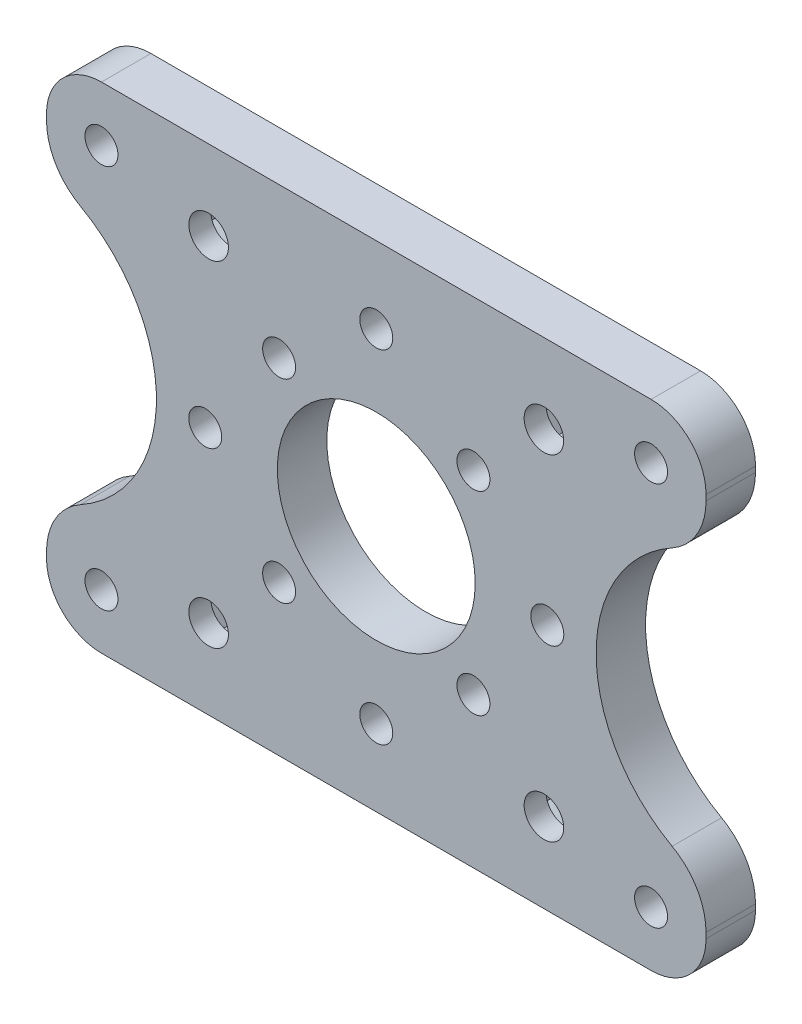
SolidWorks part; units mm, degrees
material "Tough PLA"
ref_plane "前视基准面" through (0, 0, 0) normal (0, 0, 1) x (1, 0, 0)
ref_plane "上视基准面" through (0, 0, 0) normal (0, 1, 0) x (1, 0, 0)
ref_plane "右视基准面" through (0, 0, 0) normal (1, 0, 0) x (0, 0, -1)
sketch "草图1" plane through (0, 0, 0) normal (0, 0, 1) x (1, 0, 0)
  line L0 (0, 20.9217) -> (0, -23.8045) construction
  line L1 (8.8388, 8.8388) -> (0, 0) construction
  line L6 (-30, 0) -> (30, 0) construction
  line L7 (-30, 22.5) -> (30, 22.5)
  line L8 (-30, 22.5) -> (-30, -22.5)
  line L9 (-30, -22.5) -> (30, -22.5)
  line L10 (30, 22.5) -> (30, -22.5)
  line L11 (-30, 22.5) -> (30, -22.5) construction
  line L12 (-30, -22.5) -> (30, 22.5) construction
  line L13 (-25, 17.5) -> (25, 17.5) construction
  line L14 (-25, 17.5) -> (-25, -17.5) construction
  line L15 (-25, -17.5) -> (25, -17.5) construction
  line L16 (25, 17.5) -> (25, -17.5) construction
  line L17 (-25, 17.5) -> (25, -17.5) construction
  line L18 (-25, -17.5) -> (25, 17.5) construction
  circle A1 centre (0, 0) radius 12.5 construction
  circle A3 centre (8.8388, 8.8388) radius 1.5
  circle A10 centre (0, 0) radius 9
  circle A11 centre (0, 0) radius 15.56 construction
  circle A15 centre (8.8388, -8.8388) radius 1.5
  circle A16 centre (-8.8388, -8.8388) radius 1.5
  circle A17 centre (-8.8388, 8.8388) radius 1.5
  circle A18 centre (0, -15.56) radius 1.5
  circle A19 centre (-15.56, 0) radius 1.5
  circle A20 centre (0, 15.56) radius 1.5
  circle A21 centre (15.56, 0) radius 1.5
  circle A22 centre (-25, 17.5) radius 1.5
  circle A23 centre (25, 17.5) radius 1.5
  circle A24 centre (25, -17.5) radius 1.5
  circle A25 centre (-25, -17.5) radius 1.5
  dimension "D1" = 45
  dimension "D2" = 25
  dimension "D3" = 3
  dimension "D4" = 45
  dimension "D5" = 18
  dimension "D6" = 4
  dimension "D7" = 3
  dimension "D8" = 31.12
  dimension "D9" = 4
  dimension "D12" = 50
  dimension "D13" = 3
  dimension "D10" = 60
  dimension "D11" = 35
extrude "凸台-拉伸1" add sketch "草图1" along normal blind 4.5
sketch "草图2" plane through (0, 0, 0) normal (0, 0, -1) x (-1, 0, 0)
  line L54 (-1.5, -12.9619) -> (-3, -15.56)
  line L55 (12.9619, -1.5) -> (15.56, -3)
  line L56 (15.56, -3) -> (18.1581, -1.5)
  line L57 (18.1581, -1.5) -> (18.1581, 1.5)
  line L58 (18.1581, 1.5) -> (15.56, 3)
  line L59 (15.56, 3) -> (12.9619, 1.5)
  line L60 (12.9619, 1.5) -> (12.9619, -1.5)
  line L61 (-3, -15.56) -> (-1.5, -18.1581)
  line L62 (-1.5, -18.1581) -> (1.5, -18.1581)
  line L63 (1.5, -18.1581) -> (3, -15.56)
  line L64 (3, -15.56) -> (1.5, -12.9619)
  line L65 (1.5, -12.9619) -> (-1.5, -12.9619)
  line L66 (-12.9619, 1.5) -> (-15.56, 3)
  line L67 (-15.56, 3) -> (-18.1581, 1.5)
  line L68 (-18.1581, 1.5) -> (-18.1581, -1.5)
  line L69 (-18.1581, -1.5) -> (-15.56, -3)
  line L70 (-15.56, -3) -> (-12.9619, -1.5)
  line L71 (-12.9619, -1.5) -> (-12.9619, 1.5)
  line L72 (1.5, 12.9619) -> (3, 15.56)
  line L73 (3, 15.56) -> (1.5, 18.1581)
  line L74 (1.5, 18.1581) -> (-1.5, 18.1581)
  line L75 (-1.5, 18.1581) -> (-3, 15.56)
  line L76 (-3, 15.56) -> (-1.5, 12.9619)
  line L77 (-1.5, 12.9619) -> (1.5, 12.9619)
  circle A0 centre (15.56, 0) radius 3 construction
  circle A1 centre (0, -15.56) radius 3 construction
  circle A2 centre (-15.56, 0) radius 3 construction
  circle A3 centre (0, 15.56) radius 3 construction
  circle A5 centre (0, -15.56) radius 1.5 construction
  dimension "D1" = 6
  dimension "D2" = 4
extrude "切除-拉伸1" cut sketch "草图2" against normal blind 2
fillet "圆角1" radius 5 4 edges at (-30, -22.5, 2.25) (30, -22.5, 2.25) (30, 22.5, 2.25) (-30, 22.5, 2.25)
sketch "草图4" plane through (0, 0, 4.5) normal (0, 0, 1) x (1, 0, 0)
  line L1 (-15.25, 15.25) -> (15.25, 15.25) construction
  line L2 (-15.25, 15.25) -> (-15.25, -15.25) construction
  line L3 (-15.25, -15.25) -> (15.25, -15.25) construction
  line L4 (15.25, 15.25) -> (15.25, -15.25) construction
  line L5 (-15.25, 15.25) -> (15.25, -15.25) construction
  line L6 (-15.25, -15.25) -> (15.25, 15.25) construction
  circle A0 centre (-15.25, 15.25) radius 1.8
  circle A1 centre (15.25, 15.25) radius 1.8
  circle A2 centre (15.25, -15.25) radius 1.8
  circle A3 centre (-15.25, -15.25) radius 1.8
  point P5 (0, 0)
  dimension "D2" = 3.6
  dimension "D1" = 30.5
  dimension "D3" = 4
extrude "切除-拉伸2" cut sketch "草图4" against normal up to surface (4.5 mm away) up to face at (-15.56, 0, 0)
sketch "草图5" plane through (0, 0, 0) normal (0, 0, -1) x (-1, 0, 0)
  line L0 (12.6519, 13.75) -> (15.25, 12.25)
  line L1 (-13.75, 12.6519) -> (-12.25, 15.25)
  line L2 (-12.25, 15.25) -> (-13.75, 17.8481)
  line L3 (-13.75, 17.8481) -> (-16.75, 17.8481)
  line L4 (-16.75, 17.8481) -> (-18.25, 15.25)
  line L5 (-18.25, 15.25) -> (-16.75, 12.6519)
  line L6 (-16.75, 12.6519) -> (-13.75, 12.6519)
  line L7 (15.25, 12.25) -> (17.8481, 13.75)
  line L8 (17.8481, 13.75) -> (17.8481, 16.75)
  line L9 (17.8481, 16.75) -> (15.25, 18.25)
  line L10 (15.25, 18.25) -> (12.6519, 16.75)
  line L11 (12.6519, 16.75) -> (12.6519, 13.75)
  line L12 (13.75, -12.6519) -> (12.25, -15.25)
  line L13 (12.25, -15.25) -> (13.75, -17.8481)
  line L14 (13.75, -17.8481) -> (16.75, -17.8481)
  line L15 (16.75, -17.8481) -> (18.25, -15.25)
  line L16 (18.25, -15.25) -> (16.75, -12.6519)
  line L17 (16.75, -12.6519) -> (13.75, -12.6519)
  line L18 (-12.6519, -13.75) -> (-15.25, -12.25)
  line L19 (-15.25, -12.25) -> (-17.8481, -13.75)
  line L20 (-17.8481, -13.75) -> (-17.8481, -16.75)
  line L21 (-17.8481, -16.75) -> (-15.25, -18.25)
  line L22 (-15.25, -18.25) -> (-12.6519, -16.75)
  line L23 (-12.6519, -16.75) -> (-12.6519, -13.75)
  circle A0 centre (-15.25, 15.25) radius 3 construction
  circle A1 centre (15.25, 15.25) radius 3 construction
  circle A2 centre (15.25, -15.25) radius 3 construction
  circle A3 centre (-15.25, -15.25) radius 3 construction
  circle A4 centre (15.25, 15.25) radius 1.8 construction
  dimension "D1" = 6
  dimension "D2" = 4
extrude "切除-拉伸3" cut sketch "草图5" against normal blind 2.5
sketch "草图6" plane through (0, 0, 0) normal (0, 0, -1) x (-1, 0, 0)
  line L0 (0, 0) -> (33.45, 0) construction
  line L1 (-20, 0) -> (0, 0) construction
  line L2 (-30, -17.5) -> (-30, 17.5) construction
  line L3 (-30, 13) -> (-30, -13)
  line L4 (30, -13) -> (30, 13)
  line L5 (30, 17.5) -> (30, -17.5) construction
  arc A0 (-30, 13) -> (-30, -13) centre (-33.45, 0) cw
  arc A1 (30, -13) -> (30, 13) centre (33.45, 0) cw
  dimension "D1" = 26
  dimension "D2" = 20
  dimension "D3" = 2
extrude "切除-拉伸4" cut sketch "草图6" against normal up to surface (4.5 mm away) up to face at (-13.45, -15.25, 4.5)
fillet "圆角2" radius 6 4 edges at (-30, 13, 2.25) (-30, -13, 2.25) (30, -13, 2.25) (30, 13, 2.25)
